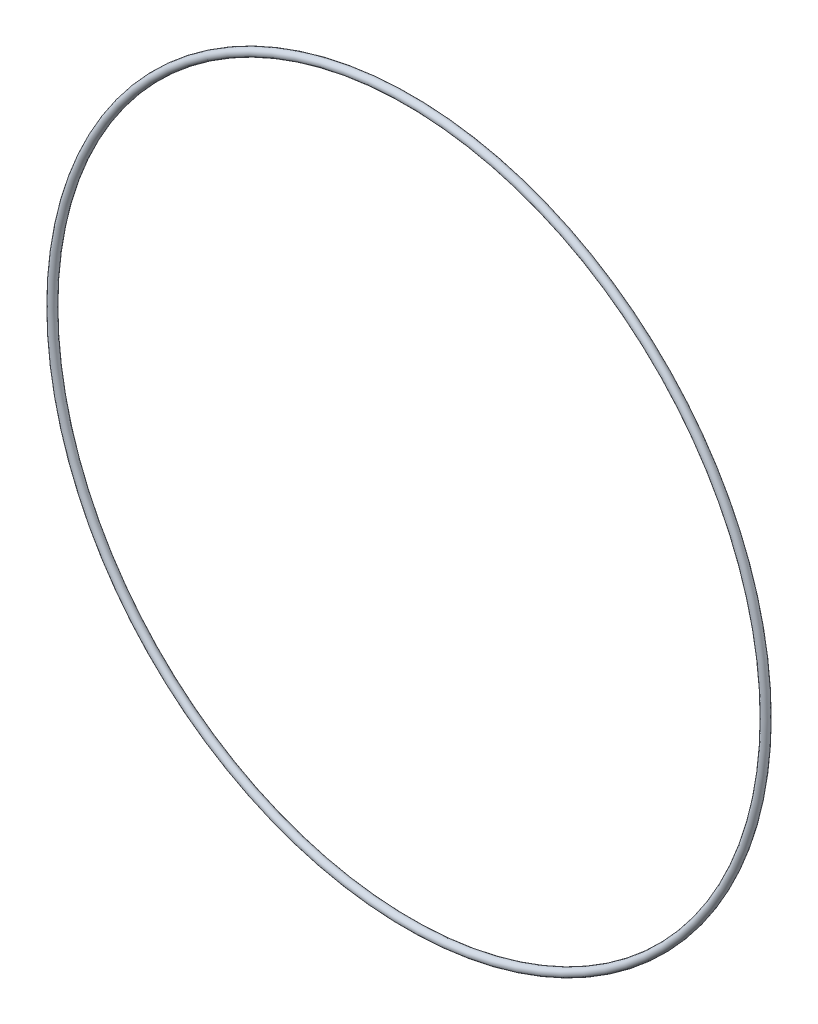
SolidWorks part; units mm, degrees
ref_plane "Front" through (0, 0, 0) normal (0, 0, 1) x (1, 0, 0)
ref_plane "Top" through (0, 0, 0) normal (0, 1, 0) x (1, 0, 0)
ref_plane "Right" through (0, 0, 0) normal (1, 0, 0) x (0, 0, -1)
sketch "Sketch1" plane through (0, 0, 0) normal (1, 0, 0) x (0, -1, 0)
  line L0 (0, -1.3081) -> (0, 1.3081) construction
  line L2 (-131.9187, 0) -> (131.9187, 0) construction
  line L3 (-117.3099, 0) -> (117.3099, 0) construction
  circle A0 centre (118.618, 0) radius 1.3081
  point P9 (117.3099, 0)
  point P10 (119.9261, 0)
  point P13 (118.618, 1.3081)
  point P14 (118.618, -1.3081)
  dimension "Width" = 2.6162
  dimension "ID" = 234.6198
revolve "Revolve1" add sketch "Sketch1" angle 360 about L0
